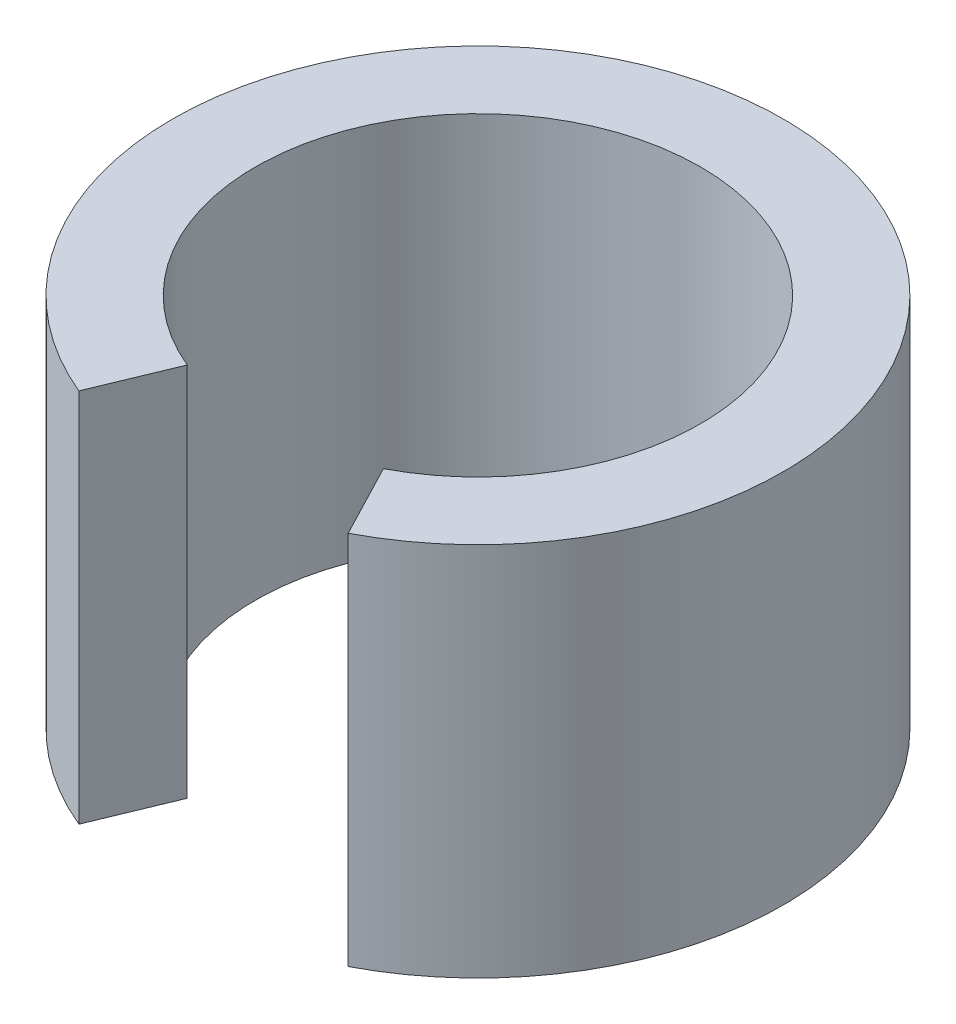
SolidWorks part; units mm, degrees
ref_plane "Front Plane" through (0, 0, 0) normal (0, 0, 1) x (1, 0, 0)
ref_plane "Top Plane" through (0, 0, 0) normal (0, 1, 0) x (1, 0, 0)
ref_plane "Right Plane" through (0, 0, 0) normal (1, 0, 0) x (0, 0, -1)
sketch "Sketch1" plane through (0, 0, 0) normal (0, 1, 0) x (1, 0, 0)
  line L0 (-1.3382, -3.2341) -> (-0.975, -2.3563)
  line L1 (1.6173, -3.1039) -> (1.1783, -2.2614)
  line L2 (0, 0) -> (-1.3382, -3.2341) construction
  line L3 (1.6173, -3.1039) -> (0, 0) construction
  arc A0 (-0.975, -2.3563) -> (1.1783, -2.2614) centre (0, 0) cw
  arc A1 (-1.3382, -3.2341) -> (1.6173, -3.1039) centre (0, 0) cw
  point P6 (-0.8747, -2.4631)
  point P7 (0.66, -2.4064)
  point P8 (0.5791, -2.4064)
  point P9 (1.2015, -2.2488)
  point P10 (1.6173, -3.1039)
  dimension "D1" = 2.55
  dimension "D2" = 3.5
  dimension "D3" = 50
extrude "Boss-Extrude1" add sketch "Sketch1" along normal blind 4.3
